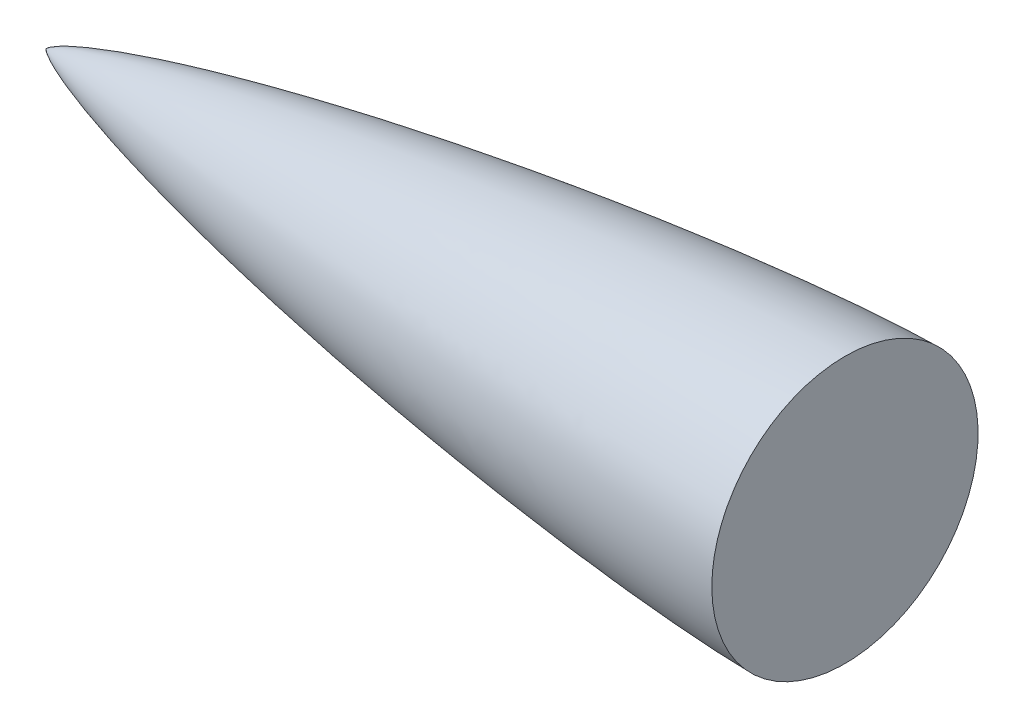
SolidWorks part; units mm, degrees
ref_plane "Front Plane" through (0, 0, 0) normal (0, 0, 1) x (1, 0, 0)
ref_plane "Top Plane" through (0, 0, 0) normal (0, 1, 0) x (1, 0, 0)
ref_plane "Right Plane" through (0, 0, 0) normal (1, 0, 0) x (0, 0, -1)
sketch "Sketch7" plane through (0, 0, 0) normal (0, 0, 1) x (1, 0, 0)
  line L0 (0, 0) -> (18, 0)
  line L1 (18, 0) -> (18, 3)
  spline S0 degree 4 poles (0, 0) (0.0013, 0.0031) (0.0043, 0.0083) (0.0104, 0.0147) (0.0195, 0.0236) (0.0317, 0.0338) (0.0507, 0.0482) (0.0829, 0.0697) (0.1394, 0.103) (0.2399, 0.1548) (0.4179, 0.2344) (0.7173, 0.3505) (1.2446, 0.5278) (2.0036, 0.7472) (2.9586, 0.9894) (4.0597, 1.2381) (5.1867, 1.4693) (6.5999, 1.7352) (8.0178, 1.9746) (9.4394, 2.1912) (10.8642, 2.3857) (12.0057, 2.5282) (13.1488, 2.6572) (14.2935, 2.7718) (15.4397, 2.8703) (16.5095, 2.9448) (17.2934, 2.9835) (17.7904, 2.9984) (18, 3) knots 0 0 0 0 0 0.000727 0.001317 0.0019 0.002799 0.004191 0.006508 0.010346 0.017109 0.028851 0.049024 0.080401 0.138459 0.201213 0.263967 0.326721 0.389475 0.514983 0.577738 0.640492 0.703246 0.766 0.828754 0.891508 0.954263 1 1 1 1 1 construction
  spline S1 degree 4 poles (0, 0) (0.0013, 0.0031) (0.0043, 0.0083) (0.0104, 0.0147) (0.0195, 0.0236) (0.0317, 0.0338) (0.0507, 0.0482) (0.0829, 0.0697) (0.1394, 0.103) (0.2399, 0.1548) (0.4179, 0.2344) (0.7173, 0.3505) (1.2446, 0.5278) (2.0036, 0.7472) (2.9586, 0.9894) (4.0597, 1.2381) (5.1867, 1.4693) (6.5999, 1.7352) (8.0178, 1.9746) (9.4394, 2.1912) (10.8642, 2.3857) (12.0057, 2.5282) (13.1488, 2.6572) (14.2935, 2.7718) (15.4397, 2.8703) (16.5095, 2.9448) (17.2934, 2.9835) (17.7904, 2.9984) (18, 3) knots 0 0 0 0 0 0.000727 0.001317 0.0019 0.002799 0.004191 0.006508 0.010346 0.017109 0.028851 0.049024 0.080401 0.138459 0.201213 0.263967 0.326721 0.389475 0.514983 0.577738 0.640492 0.703246 0.766 0.828754 0.891508 0.954263 1 1 1 1 1
  dimension "D1" = 18
revolve "Revolve7" add sketch "Sketch7" angle 360 about L0
